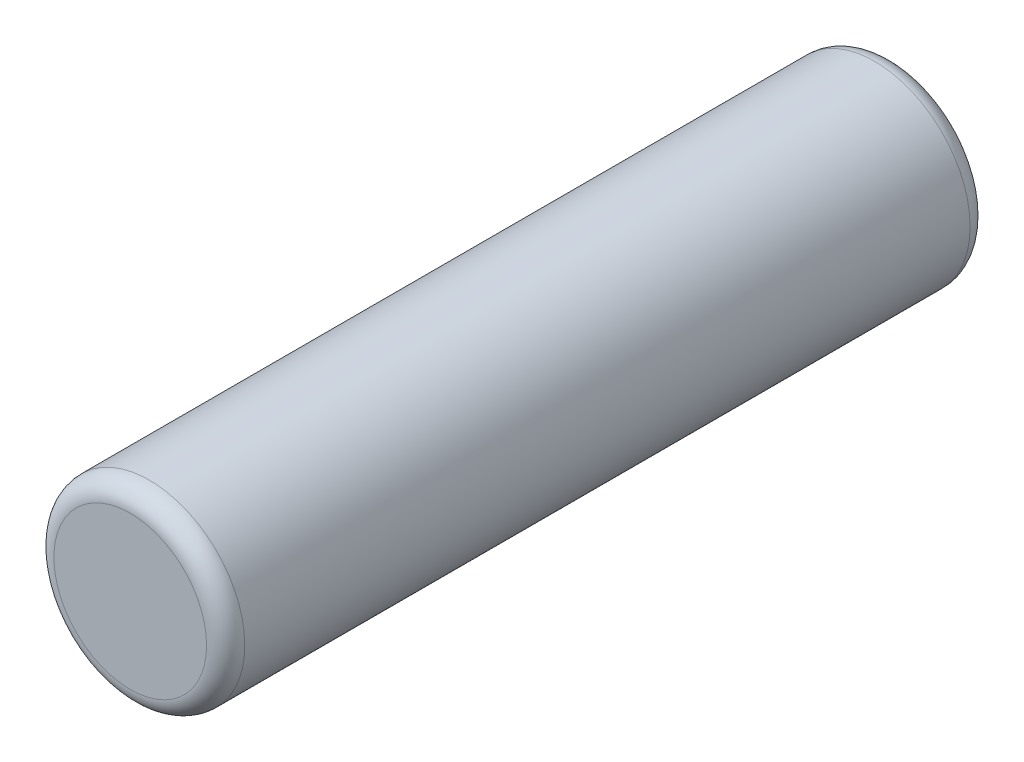
SolidWorks part; units mm, degrees
ref_plane "Front Plane" through (0, 0, 0) normal (0, 0, 1) x (1, 0, 0)
ref_plane "Top Plane" through (0, 0, 0) normal (0, 1, 0) x (1, 0, 0)
ref_plane "Right Plane" through (0, 0, 0) normal (1, 0, 0) x (0, 0, -1)
sketch "Sketch1" plane through (0, 0, 0) normal (0, 0, 1) x (1, 0, 0)
  circle A0 centre (0, 0) radius 2.5
  dimension "D1" = 5
extrude "Boss-Extrude1" add sketch "Sketch1" along normal blind 20
fillet "Fillet1" radius 0.5 2 edges at (2.5, 0, 0) (2.5, 0, 20)
